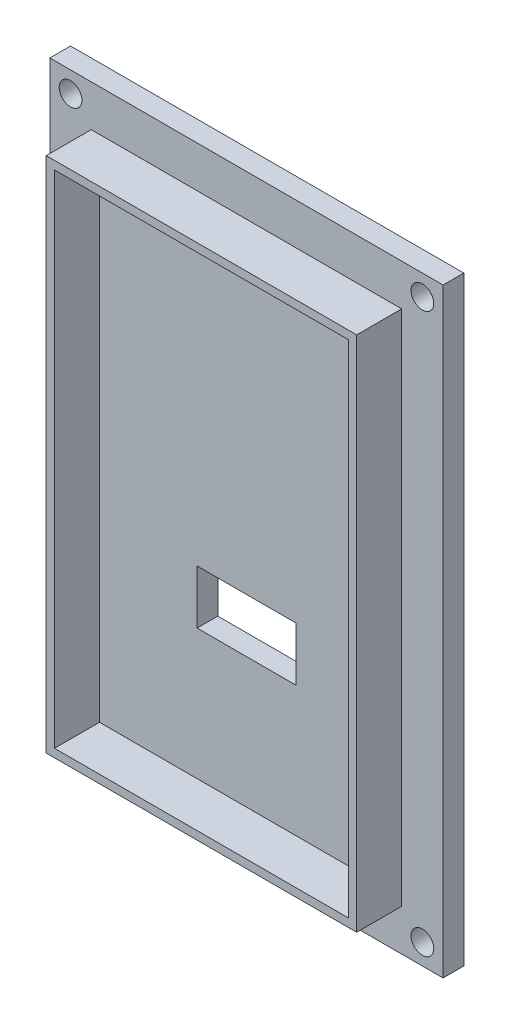
SolidWorks part; units mm, degrees
ref_plane "Front Plane" through (0, 0, 0) normal (0, 0, 1) x (1, 0, 0)
ref_plane "Top Plane" through (0, 0, 0) normal (0, 1, 0) x (1, 0, 0)
ref_plane "Right Plane" through (0, 0, 0) normal (1, 0, 0) x (0, 0, -1)
ref_plane "背板内侧面" through (0, 0, -4.35) normal (0, 0, 1) x (1, 0, 0)
sketch "背板_草图" plane through (0, 0, -4.35) normal (0, 0, 1) x (1, 0, 0)
  line L1 (-4, -54) -> (34, -54)
  line L2 (-4, -54) -> (-4, 4)
  line L3 (-4, 4) -> (34, 4)
  line L4 (34, -54) -> (34, 4)
  dimension "D1" = 38
  dimension "D2" = 58
extrude "背板" add sketch "背板_草图" against normal blind 2
sketch "PCB压框_草图" plane through (0, 0, -4.35) normal (0, 0, 1) x (1, 0, 0)
  line L1 (0, -50) -> (30, -50)
  line L2 (0, -50) -> (0, 0)
  line L3 (0, 0) -> (30, 0)
  line L4 (30, -50) -> (30, 0)
  line L6 (0.8, -49.2) -> (29.2, -49.2)
  line L7 (0.8, -49.2) -> (0.8, -0.8)
  line L8 (0.8, -0.8) -> (29.2, -0.8)
  line L9 (29.2, -49.2) -> (29.2, -0.8)
  dimension "D1" = 30
  dimension "D2" = 50
extrude "PCB压框" add sketch "PCB压框_草图" along normal blind 4.35
sketch "螺丝过孔x4_草图" plane through (0, 0, -4.35) normal (0, 0, 1) x (1, 0, 0)
  circle A0 centre (-2, 2) radius 1.1
  circle A1 centre (32, 2) radius 1.1
  circle A2 centre (-2, -52) radius 1.1
  circle A3 centre (32, -52) radius 1.1
  dimension "D1" = 2.2
extrude "螺丝过孔x4" cut sketch "螺丝过孔x4_草图" against normal through all
sketch "TypeC开孔_草图" plane through (0, 0, -4.35) normal (0, 0, 1) x (1, 0, 0)
  line L1 (10.23, -36.6) -> (19.77, -36.6)
  line L2 (10.23, -36.6) -> (10.23, -31.4)
  line L3 (10.23, -31.4) -> (19.77, -31.4)
  line L4 (19.77, -36.6) -> (19.77, -31.4)
  dimension "D1" = 9.54
  dimension "D2" = 5.2
extrude "TypeC开孔" cut sketch "TypeC开孔_草图" against normal through all
ref_plane "刻字面" through (0, 0, -6.35) normal (0, 0, 1) x (1, 0, 0)
sketch "刻字_背板_草图" plane through (0, 0, -6.35) normal (0, 0, 1) x (1, 0, 0)
  line L0 (15.3152, -12.0263) -> (15.4334, -12.0582)
  line L1 (15.4334, -12.0582) -> (15.5513, -12.0896)
  line L2 (15.5513, -12.0896) -> (15.6687, -12.1202)
  line L3 (15.6687, -12.1202) -> (15.7856, -12.1502)
  line L4 (15.7856, -12.1502) -> (15.9021, -12.1795)
  line L5 (15.9021, -12.1795) -> (16.0182, -12.2081)
  line L6 (16.0182, -12.2081) -> (15.9015, -12.2605)
  line L7 (15.9015, -12.2605) -> (15.7722, -12.3154)
  line L8 (15.7722, -12.3154) -> (15.6303, -12.3727)
  line L9 (15.6303, -12.3727) -> (15.4759, -12.4325)
  line L10 (15.4759, -12.4325) -> (15.3089, -12.4948)
  line L11 (15.3089, -12.4948) -> (15.1293, -12.5596)
  line L12 (15.1293, -12.5596) -> (15.1777, -12.8239)
  line L13 (15.1777, -12.8239) -> (15.2339, -13.0566)
  line L14 (15.2339, -13.0566) -> (15.298, -13.2576)
  line L15 (15.298, -13.2576) -> (15.3699, -13.4269)
  line L16 (15.3699, -13.4269) -> (15.4497, -13.5646)
  line L17 (15.4497, -13.5646) -> (15.5374, -13.6707)
  line L18 (15.5374, -13.6707) -> (15.6389, -13.7534)
  line L19 (15.6389, -13.7534) -> (15.7605, -13.8211)
  line L20 (15.7605, -13.8211) -> (15.902, -13.8737)
  line L21 (15.902, -13.8737) -> (16.0635, -13.9113)
  line L22 (16.0635, -13.9113) -> (16.245, -13.9339)
  line L23 (16.245, -13.9339) -> (16.4465, -13.9414)
  line L24 (16.4465, -13.9414) -> (17.7071, -13.9414)
  line L25 (17.7071, -13.9414) -> (18.0552, -13.9102)
  line L26 (18.0552, -13.9102) -> (18.3401, -13.8166)
  line L27 (18.3401, -13.8166) -> (18.5616, -13.6606)
  line L28 (18.5616, -13.6606) -> (18.7199, -13.4422)
  line L29 (18.7199, -13.4422) -> (18.8148, -13.1614)
  line L30 (18.8148, -13.1614) -> (18.8465, -12.8182)
  line L31 (18.8465, -12.8182) -> (18.8465, -11)
  line L32 (18.8465, -11) -> (17.796, -11)
  line L33 (17.796, -11) -> (17.796, -11.7475)
  line L34 (17.796, -11.7475) -> (17.4321, -11.6547)
  line L35 (17.4321, -11.6547) -> (17.0759, -11.5567)
  line L36 (17.0759, -11.5567) -> (16.7273, -11.4535)
  line L37 (16.7273, -11.4535) -> (16.3863, -11.3452)
  line L38 (16.3863, -11.3452) -> (16.053, -11.2318)
  line L39 (16.053, -11.2318) -> (15.7273, -11.1131)
  line L40 (15.7273, -11.1131) -> (15.3152, -12.0263)
  line L41 (17.796, -12.5879) -> (17.796, -12.6485)
  line L42 (17.796, -12.6485) -> (17.7841, -12.767)
  line L43 (17.7841, -12.767) -> (17.7484, -12.864)
  line L44 (17.7484, -12.864) -> (17.6889, -12.9394)
  line L45 (17.6889, -12.9394) -> (17.6056, -12.9933)
  line L46 (17.6056, -12.9933) -> (17.4985, -13.0256)
  line L47 (17.4985, -13.0256) -> (17.3677, -13.0364)
  line L48 (17.3677, -13.0364) -> (16.7131, -13.0364)
  line L49 (16.7131, -13.0364) -> (16.6186, -13.0333)
  line L50 (16.6186, -13.0333) -> (16.5342, -13.0242)
  line L51 (16.5342, -13.0242) -> (16.4601, -13.0091)
  line L52 (16.4601, -13.0091) -> (16.3962, -12.9879)
  line L53 (16.3962, -12.9879) -> (16.3425, -12.9606)
  line L54 (16.3425, -12.9606) -> (16.299, -12.9273)
  line L55 (16.299, -12.9273) -> (16.2619, -12.8777)
  line L56 (16.2619, -12.8777) -> (16.2274, -12.8016)
  line L57 (16.2274, -12.8016) -> (16.1955, -12.699)
  line L58 (16.1955, -12.699) -> (16.1661, -12.5699)
  line L59 (16.1661, -12.5699) -> (16.1393, -12.4144)
  line L60 (16.1393, -12.4144) -> (16.1152, -12.2323)
  line L61 (16.1152, -12.2323) -> (16.3998, -12.2994)
  line L62 (16.3998, -12.2994) -> (16.6826, -12.3634)
  line L63 (16.6826, -12.3634) -> (16.9636, -12.4242)
  line L64 (16.9636, -12.4242) -> (17.2429, -12.4819)
  line L65 (17.2429, -12.4819) -> (17.5203, -12.5365)
  line L66 (17.5203, -12.5365) -> (17.796, -12.5879)
  line L67 (23.0485, -13.7394) -> (23.1455, -12.8586)
  line L68 (23.1455, -12.8586) -> (20.8263, -12.6081)
  line L69 (20.8263, -12.6081) -> (20.8263, -12.301)
  line L70 (20.8263, -12.301) -> (22.9273, -12.301)
  line L71 (22.9273, -12.301) -> (22.9273, -11.5172)
  line L72 (22.9273, -11.5172) -> (20.8263, -11.5172)
  line L73 (20.8263, -11.5172) -> (20.8263, -11.0162)
  line L74 (20.8263, -11.0162) -> (19.7758, -11.0162)
  line L75 (19.7758, -11.0162) -> (19.7758, -13.9818)
  line L76 (19.7758, -13.9818) -> (20.8263, -13.9818)
  line L77 (20.8263, -13.9818) -> (20.8263, -13.4323)
  line L78 (20.8263, -13.4323) -> (23.0485, -13.7394)
  line L79 (21.1495, -18.9354) -> (22.2808, -18.9354)
  line L80 (22.2808, -18.9354) -> (22.2808, -14.2727)
  line L81 (22.2808, -14.2727) -> (16.0586, -14.2727)
  line L82 (16.0586, -14.2727) -> (16.0586, -17.6909)
  line L83 (16.0586, -17.6909) -> (16.065, -17.86)
  line L84 (16.065, -17.86) -> (16.0844, -18.0144)
  line L85 (16.0844, -18.0144) -> (16.1167, -18.154)
  line L86 (16.1167, -18.154) -> (16.1618, -18.279)
  line L87 (16.1618, -18.279) -> (16.2199, -18.3893)
  line L88 (16.2199, -18.3893) -> (16.2909, -18.4848)
  line L89 (16.2909, -18.4848) -> (16.371, -18.5679)
  line L90 (16.371, -18.5679) -> (16.4566, -18.6406)
  line L91 (16.4566, -18.6406) -> (16.5475, -18.703)
  line L92 (16.5475, -18.703) -> (16.6438, -18.7551)
  line L93 (16.6438, -18.7551) -> (16.7455, -18.7969)
  line L94 (16.7455, -18.7969) -> (16.8525, -18.8283)
  line L95 (16.8525, -18.8283) -> (17.0016, -18.852)
  line L96 (17.0016, -18.852) -> (17.2294, -18.8707)
  line L97 (17.2294, -18.8707) -> (17.5359, -18.8843)
  line L98 (17.5359, -18.8843) -> (17.921, -18.8929)
  line L99 (17.921, -18.8929) -> (18.3848, -18.8965)
  line L100 (18.3848, -18.8965) -> (18.9273, -18.8949)
  line L101 (18.9273, -18.8949) -> (18.9569, -18.7486)
  line L102 (18.9569, -18.7486) -> (18.9919, -18.5951)
  line L103 (18.9919, -18.5951) -> (19.0323, -18.4343)
  line L104 (19.0323, -18.4343) -> (19.0781, -18.2664)
  line L105 (19.0781, -18.2664) -> (19.1293, -18.0914)
  line L106 (19.1293, -18.0914) -> (19.1859, -17.9091)
  line L107 (19.1859, -17.9091) -> (18.9691, -17.9165)
  line L108 (18.9691, -17.9165) -> (18.7365, -17.9226)
  line L109 (18.7365, -17.9226) -> (18.4879, -17.9273)
  line L110 (18.4879, -17.9273) -> (18.2233, -17.9306)
  line L111 (18.2233, -17.9306) -> (17.9429, -17.9327)
  line L112 (17.9429, -17.9327) -> (17.6465, -17.9333)
  line L113 (17.6465, -17.9333) -> (17.5103, -17.9196)
  line L114 (17.5103, -17.9196) -> (17.3982, -17.8786)
  line L115 (17.3982, -17.8786) -> (17.3101, -17.8101)
  line L116 (17.3101, -17.8101) -> (17.246, -17.7143)
  line L117 (17.246, -17.7143) -> (17.2059, -17.591)
  line L118 (17.2059, -17.591) -> (17.1899, -17.4404)
  line L119 (17.1899, -17.4404) -> (21.1495, -17.4404)
  line L120 (21.1495, -17.4404) -> (21.1495, -18.9354)
  line L121 (17.1899, -15.097) -> (21.1495, -15.097)
  line L122 (21.1495, -15.097) -> (21.1495, -15.5414)
  line L123 (21.1495, -15.5414) -> (17.1899, -15.5414)
  line L124 (17.1899, -15.5414) -> (17.1899, -15.097)
  line L125 (21.1495, -16.7131) -> (17.1899, -16.7131)
  line L126 (17.1899, -16.7131) -> (17.1899, -16.2687)
  line L127 (17.1899, -16.2687) -> (21.1495, -16.2687)
  line L128 (21.1495, -16.2687) -> (21.1495, -16.7131)
  line L129 (14.903, -15.8566) -> (14.674, -15.4642)
  line L130 (14.674, -15.4642) -> (14.4689, -15.079)
  line L131 (14.4689, -15.079) -> (14.2879, -14.701)
  line L132 (14.2879, -14.701) -> (14.1309, -14.3302)
  line L133 (14.1309, -14.3302) -> (13.9979, -13.9666)
  line L134 (13.9979, -13.9666) -> (13.8889, -13.6101)
  line L135 (13.8889, -13.6101) -> (14.8303, -13.6101)
  line L136 (14.8303, -13.6101) -> (14.8303, -12.5515)
  line L137 (14.8303, -12.5515) -> (13.8768, -12.5515)
  line L138 (13.8768, -12.5515) -> (13.8768, -11.0566)
  line L139 (13.8768, -11.0566) -> (12.8263, -11.0566)
  line L140 (12.8263, -11.0566) -> (12.8263, -12.5515)
  line L141 (12.8263, -12.5515) -> (11.9697, -12.5515)
  line L142 (11.9697, -12.5515) -> (11.9697, -13.6101)
  line L143 (11.9697, -13.6101) -> (12.8263, -13.6101)
  line L144 (12.8263, -13.6101) -> (12.8263, -14.3374)
  line L145 (12.8263, -14.3374) -> (12.662, -14.4211)
  line L146 (12.662, -14.4211) -> (12.4949, -14.508)
  line L147 (12.4949, -14.508) -> (12.3253, -14.598)
  line L148 (12.3253, -14.598) -> (12.1529, -14.6911)
  line L149 (12.1529, -14.6911) -> (11.9778, -14.7874)
  line L150 (11.9778, -14.7874) -> (11.8, -14.8869)
  line L151 (11.8, -14.8869) -> (12.3091, -15.8081)
  line L152 (12.3091, -15.8081) -> (12.3897, -15.7542)
  line L153 (12.3897, -15.7542) -> (12.4725, -15.7003)
  line L154 (12.4725, -15.7003) -> (12.5576, -15.6465)
  line L155 (12.5576, -15.6465) -> (12.6449, -15.5926)
  line L156 (12.6449, -15.5926) -> (12.7345, -15.5387)
  line L157 (12.7345, -15.5387) -> (12.8263, -15.4848)
  line L158 (12.8263, -15.4848) -> (12.8263, -18.9434)
  line L159 (12.8263, -18.9434) -> (13.8768, -18.9434)
  line L160 (13.8768, -18.9434) -> (13.8768, -15.8444)
  line L161 (13.8768, -15.8444) -> (13.9825, -16.0863)
  line L162 (13.9825, -16.0863) -> (14.0949, -16.327)
  line L163 (14.0949, -16.327) -> (14.2141, -16.5667)
  line L164 (14.2141, -16.5667) -> (14.3401, -16.8052)
  line L165 (14.3401, -16.8052) -> (14.4727, -17.0425)
  line L166 (14.4727, -17.0425) -> (14.6121, -17.2788)
  line L167 (14.6121, -17.2788) -> (14.6606, -17.0215)
  line L168 (14.6606, -17.0215) -> (14.7091, -16.7724)
  line L169 (14.7091, -16.7724) -> (14.7576, -16.5313)
  line L170 (14.7576, -16.5313) -> (14.8061, -16.2983)
  line L171 (14.8061, -16.2983) -> (14.8545, -16.0734)
  line L172 (14.8545, -16.0734) -> (14.903, -15.8566)
  line L173 (7.3152, -11.1616) -> (6.9596, -12.2444)
  line L174 (6.9596, -12.2444) -> (7.4256, -12.325)
  line L175 (7.4256, -12.325) -> (7.9562, -12.3998)
  line L176 (7.9562, -12.3998) -> (8.5515, -12.4687)
  line L177 (8.5515, -12.4687) -> (9.2114, -12.5318)
  line L178 (9.2114, -12.5318) -> (9.936, -12.589)
  line L179 (9.936, -12.589) -> (10.7253, -12.6404)
  line L180 (10.7253, -12.6404) -> (10.7253, -13.4081)
  line L181 (10.7253, -13.4081) -> (7.1939, -13.4081)
  line L182 (7.1939, -13.4081) -> (7.1939, -14.4424)
  line L183 (7.1939, -14.4424) -> (7.3311, -14.9169)
  line L184 (7.3311, -14.9169) -> (7.4893, -15.3708)
  line L185 (7.4893, -15.3708) -> (7.6687, -15.804)
  line L186 (7.6687, -15.804) -> (7.8691, -16.2166)
  line L187 (7.8691, -16.2166) -> (8.0907, -16.6085)
  line L188 (8.0907, -16.6085) -> (8.3333, -16.9798)
  line L189 (8.3333, -16.9798) -> (8.1172, -17.1603)
  line L190 (8.1172, -17.1603) -> (7.8889, -17.3219)
  line L191 (7.8889, -17.3219) -> (7.6485, -17.4646)
  line L192 (7.6485, -17.4646) -> (7.396, -17.5886)
  line L193 (7.396, -17.5886) -> (7.1313, -17.6936)
  line L194 (7.1313, -17.6936) -> (6.8545, -17.7798)
  line L195 (6.8545, -17.7798) -> (6.978, -17.9596)
  line L196 (6.978, -17.9596) -> (7.1006, -18.1488)
  line L197 (7.1006, -18.1488) -> (7.2222, -18.3475)
  line L198 (7.2222, -18.3475) -> (7.343, -18.5556)
  line L199 (7.343, -18.5556) -> (7.4629, -18.7731)
  line L200 (7.4629, -18.7731) -> (7.5818, -19)
  line L201 (7.5818, -19) -> (7.8587, -18.8379)
  line L202 (7.8587, -18.8379) -> (8.1237, -18.6642)
  line L203 (8.1237, -18.6642) -> (8.3768, -18.4788)
  line L204 (8.3768, -18.4788) -> (8.618, -18.2817)
  line L205 (8.618, -18.2817) -> (8.8473, -18.073)
  line L206 (8.8473, -18.073) -> (9.0646, -17.8525)
  line L207 (9.0646, -17.8525) -> (9.2951, -18.0694)
  line L208 (9.2951, -18.0694) -> (9.5365, -18.2754)
  line L209 (9.5365, -18.2754) -> (9.7889, -18.4707)
  line L210 (9.7889, -18.4707) -> (10.0523, -18.6552)
  line L211 (10.0523, -18.6552) -> (10.3267, -18.829)
  line L212 (10.3267, -18.829) -> (10.6121, -18.9919)
  line L213 (10.6121, -18.9919) -> (10.7147, -18.8061)
  line L214 (10.7147, -18.8061) -> (10.8177, -18.6256)
  line L215 (10.8177, -18.6256) -> (10.9212, -18.4505)
  line L216 (10.9212, -18.4505) -> (11.0251, -18.2808)
  line L217 (11.0251, -18.2808) -> (11.1295, -18.1165)
  line L218 (11.1295, -18.1165) -> (11.2343, -17.9576)
  line L219 (11.2343, -17.9576) -> (10.9543, -17.8129)
  line L220 (10.9543, -17.8129) -> (10.688, -17.659)
  line L221 (10.688, -17.659) -> (10.4354, -17.496)
  line L222 (10.4354, -17.496) -> (10.1964, -17.3237)
  line L223 (10.1964, -17.3237) -> (9.9712, -17.1422)
  line L224 (9.9712, -17.1422) -> (9.7596, -16.9515)
  line L225 (9.7596, -16.9515) -> (9.9198, -16.6805)
  line L226 (9.9198, -16.6805) -> (10.0689, -16.398)
  line L227 (10.0689, -16.398) -> (10.2071, -16.104)
  line L228 (10.2071, -16.104) -> (10.3342, -15.7987)
  line L229 (10.3342, -15.7987) -> (10.4504, -15.4818)
  line L230 (10.4504, -15.4818) -> (10.5556, -15.1535)
  line L231 (10.5556, -15.1535) -> (9.7717, -14.4424)
  line L232 (9.7717, -14.4424) -> (10.7253, -14.4424)
  line L233 (10.7253, -14.4424) -> (10.7253, -15.1212)
  line L234 (10.7253, -15.1212) -> (10.7594, -15.8642)
  line L235 (10.7594, -15.8642) -> (10.8617, -16.5686)
  line L236 (10.8617, -16.5686) -> (11.0323, -17.2343)
  line L237 (11.0323, -17.2343) -> (11.2712, -17.8615)
  line L238 (11.2712, -17.8615) -> (11.5782, -18.4501)
  line L239 (11.5782, -18.4501) -> (11.9535, -19)
  line L240 (11.9535, -19) -> (12.0862, -18.8352)
  line L241 (12.0862, -18.8352) -> (12.2202, -18.675)
  line L242 (12.2202, -18.675) -> (12.3556, -18.5192)
  line L243 (12.3556, -18.5192) -> (12.4923, -18.3679)
  line L244 (12.4923, -18.3679) -> (12.6303, -18.2211)
  line L245 (12.6303, -18.2211) -> (12.7697, -18.0788)
  line L246 (12.7697, -18.0788) -> (12.466, -17.6521)
  line L247 (12.466, -17.6521) -> (12.2175, -17.1692)
  line L248 (12.2175, -17.1692) -> (12.0242, -16.6303)
  line L249 (12.0242, -16.6303) -> (11.8862, -16.0352)
  line L250 (11.8862, -16.0352) -> (11.8034, -15.3841)
  line L251 (11.8034, -15.3841) -> (11.7758, -14.6768)
  line L252 (11.7758, -14.6768) -> (11.7758, -11.5899)
  line L253 (11.7758, -11.5899) -> (10.846, -11.5398)
  line L254 (10.846, -11.5398) -> (9.9908, -11.4813)
  line L255 (9.9908, -11.4813) -> (9.2101, -11.4141)
  line L256 (9.2101, -11.4141) -> (8.5039, -11.3385)
  line L257 (8.5039, -11.3385) -> (7.8723, -11.2543)
  line L258 (7.8723, -11.2543) -> (7.3152, -11.1616)
  line L259 (9.0525, -16.1152) -> (8.8974, -15.8622)
  line L260 (8.8974, -15.8622) -> (8.758, -15.5989)
  line L261 (8.758, -15.5989) -> (8.6343, -15.3253)
  line L262 (8.6343, -15.3253) -> (8.5264, -15.0413)
  line L263 (8.5264, -15.0413) -> (8.4341, -14.747)
  line L264 (8.4341, -14.747) -> (8.3576, -14.4424)
  line L265 (8.3576, -14.4424) -> (9.7636, -14.4424)
  line L266 (9.7636, -14.4424) -> (9.6687, -14.7582)
  line L267 (9.6687, -14.7582) -> (9.5643, -15.0593)
  line L268 (9.5643, -15.0593) -> (9.4505, -15.3455)
  line L269 (9.4505, -15.3455) -> (9.3273, -15.6168)
  line L270 (9.3273, -15.6168) -> (9.1946, -15.8734)
  line L271 (9.1946, -15.8734) -> (9.0525, -16.1152)
extrude "刻字_背板" cut sketch "刻字_背板_草图" along normal blind 0.3
